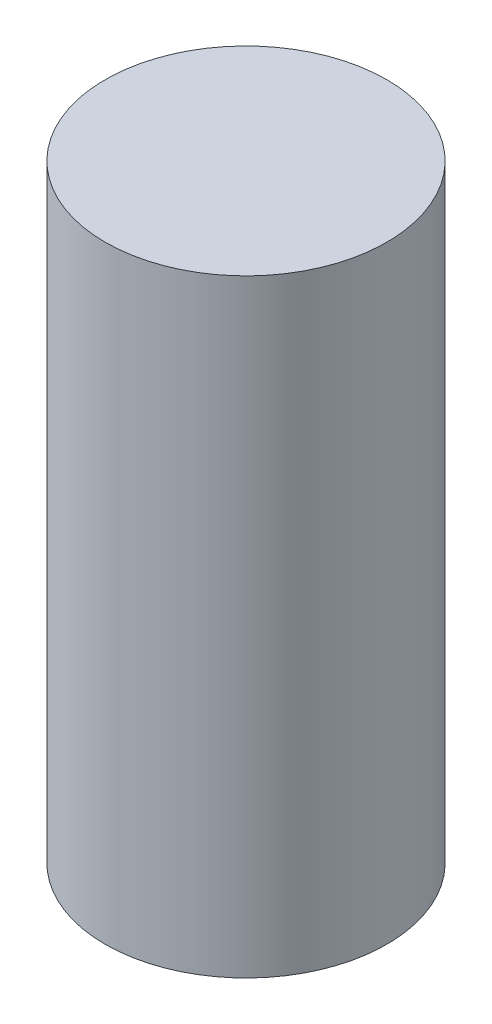
SolidWorks part; units mm, degrees
ref_plane "Front Plane" through (0, 0, 0) normal (0, 0, 1) x (1, 0, 0)
ref_plane "Top Plane" through (0, 0, 0) normal (0, 1, 0) x (1, 0, 0)
ref_plane "Right Plane" through (0, 0, 0) normal (1, 0, 0) x (0, 0, -1)
other "Configuration Table"
sketch "Sketch1" plane through (0, 0, 0) normal (0, 1, 0) x (1, 0, 0)
  circle A0 centre (0, 0) radius 44
extrude "KOLA1L_govde_D88" add sketch "Sketch1" along normal blind 190 separate body
